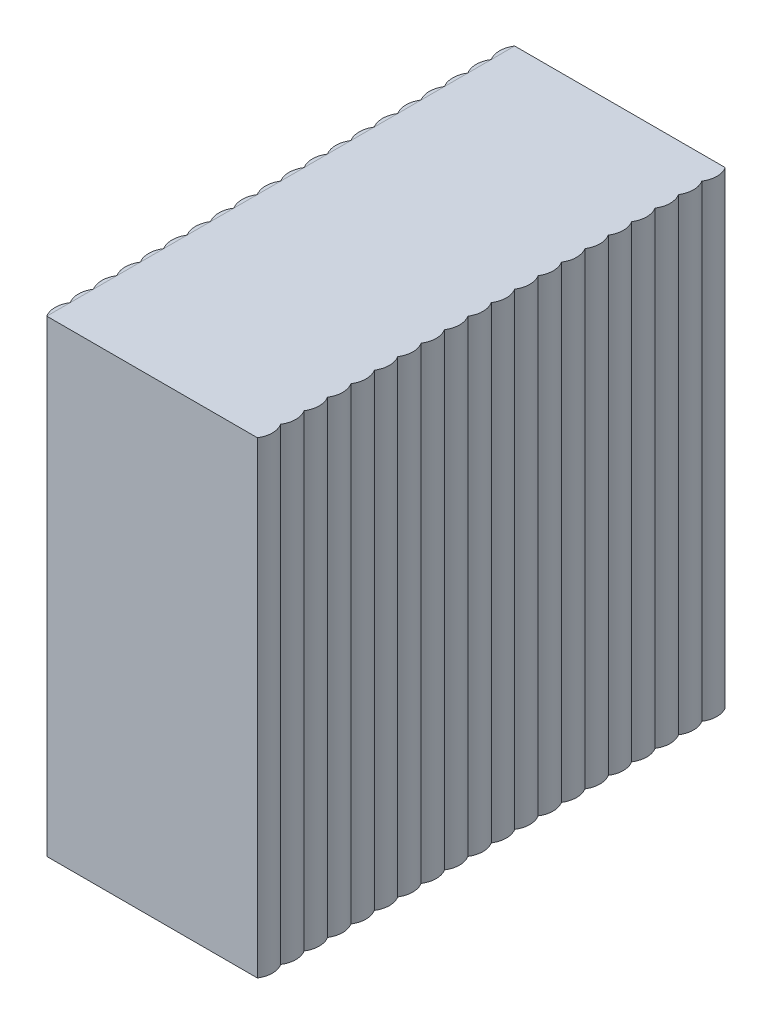
SolidWorks part; units mm, degrees
ref_plane "前视基准面" through (0, 0, 0) normal (0, 0, 1) x (1, 0, 0)
ref_plane "上视基准面" through (0, 0, 0) normal (0, 1, 0) x (1, 0, 0)
ref_plane "右视基准面" through (0, 0, 0) normal (1, 0, 0) x (0, 0, -1)
sketch "草图1" plane through (0, 0, 0) normal (1, 0, 0) x (0, 0, -1)
  line L1 (0, 0) -> (5, 0)
  line L2 (0, 0) -> (0, 5)
  line L3 (0, 5) -> (5, 5)
  line L4 (5, 0) -> (5, 5)
  dimension "D1" = 5
  dimension "D2" = 5
extrude "凸台-拉伸1" add sketch "草图1" along normal blind 2.25
sketch "草图3" plane through (0, 0, 0) normal (0, -1, 0) x (1, 0, 0)
  line L0 (0.1967, -4.875) -> (0.1967, -4.625) construction
  line L2 (-0.0364, -5.0397) -> (-0.0364, -0.0247)
  line L3 (0, -5) -> (0, 0)
  circle A0 centre (0.1967, -4.875) radius 0.2331
  circle A1 centre (0.1967, -4.625) radius 0.2331
  circle A2 centre (0.1967, -4.375) radius 0.2331
  circle A3 centre (0.1967, -4.125) radius 0.2331
  circle A4 centre (0.1967, -3.875) radius 0.2331
  circle A5 centre (0.1967, -3.625) radius 0.2331
  circle A6 centre (0.1967, -3.375) radius 0.2331
  circle A7 centre (0.1967, -3.125) radius 0.2331
  circle A8 centre (0.1967, -2.875) radius 0.2331
  circle A9 centre (0.1967, -2.625) radius 0.2331
  circle A10 centre (0.1967, -2.375) radius 0.2331
  circle A11 centre (0.1967, -2.125) radius 0.2331
  circle A12 centre (0.1967, -1.875) radius 0.2331
  circle A13 centre (0.1967, -1.625) radius 0.2331
  circle A14 centre (0.1967, -1.375) radius 0.2331
  circle A15 centre (0.1967, -1.125) radius 0.2331
  circle A16 centre (0.1967, -0.875) radius 0.2331
  circle A17 centre (0.1967, -0.625) radius 0.2331
  circle A18 centre (0.1967, -0.375) radius 0.2331
  circle A19 centre (0.1967, -0.125) radius 0.2331
  line M21 (0, 0) -> (0, -5)
  dimension "D1" = 20
  dimension "D2" = 0.25
extrude "凸台-拉伸3" add sketch "草图3" against normal up to surface (5 mm away) separate body contours L3 A0 | L3 A1 | L3 A2 | L3 A3 | L3 A4 | L3 A5 | L3 A6 | L3 A7 | L3 A8 | L3 A9 | L3 A10 | L3 A11 | L3 A12 | L3 A13 | L3 A14 | L3 A15 | L3 A16 | L3 A17 | L3 A18 | A19 M21 | L2
ref_plane "基准面1" through (1.125, 0, 0) normal (1, 0, 0) x (0, 0, -1)
mirror "镜向1" about plane through (1.125, 0, 0) normal (1, 0, 0) of "凸台-拉伸3"
